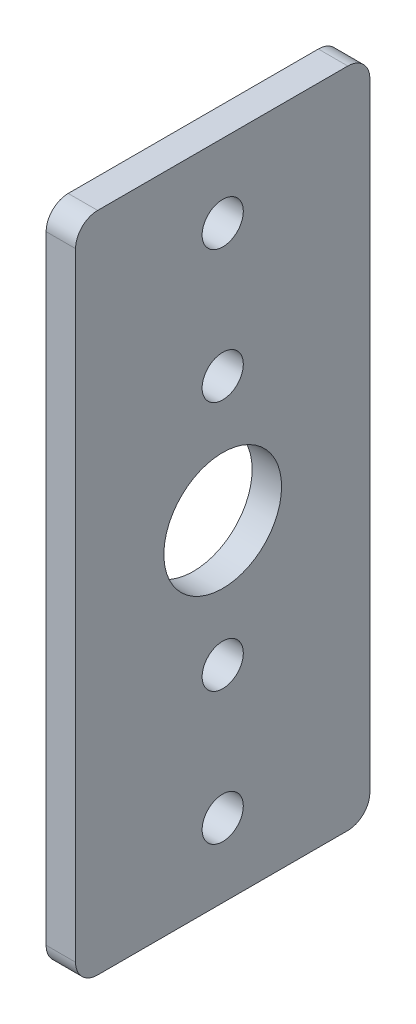
SolidWorks part; units mm, degrees
ref_plane "Front Plane" through (0, 0, 0) normal (0, 0, 1) x (1, 0, 0)
ref_plane "Top Plane" through (0, 0, 0) normal (0, 1, 0) x (1, 0, 0)
ref_plane "Right Plane" through (0, 0, 0) normal (1, 0, 0) x (0, 0, -1)
sketch "Sketch2" plane through (0, 0, 0) normal (1, 0, 0) x (0, 0, -1)
  line L1 (-9.3941, -41.2566) -> (10.6059, -41.2566)
  line L2 (-9.3941, -41.2566) -> (-9.3941, -86.2566)
  line L3 (-9.3941, -86.2566) -> (10.6059, -86.2566)
  line L4 (10.6059, -41.2566) -> (10.6059, -86.2566)
  circle A8 centre (0.6059, -63.7566) radius 4
  circle A11 centre (0.6059, -46.2566) radius 1.4
  circle A12 centre (0.6059, -55.2566) radius 1.4
  circle A13 centre (0.6059, -72.2566) radius 1.4
  circle A14 centre (0.6059, -81.2566) radius 1.4
extrude "Boss-Extrude1" add sketch "Sketch2" along normal blind 2
fillet "Fillet1" radius 1.5 4 edges at (1, -41.2566, -10.6059) (1, -41.2566, 9.3941) (1, -86.2566, 9.3941) (1, -86.2566, -10.6059)
